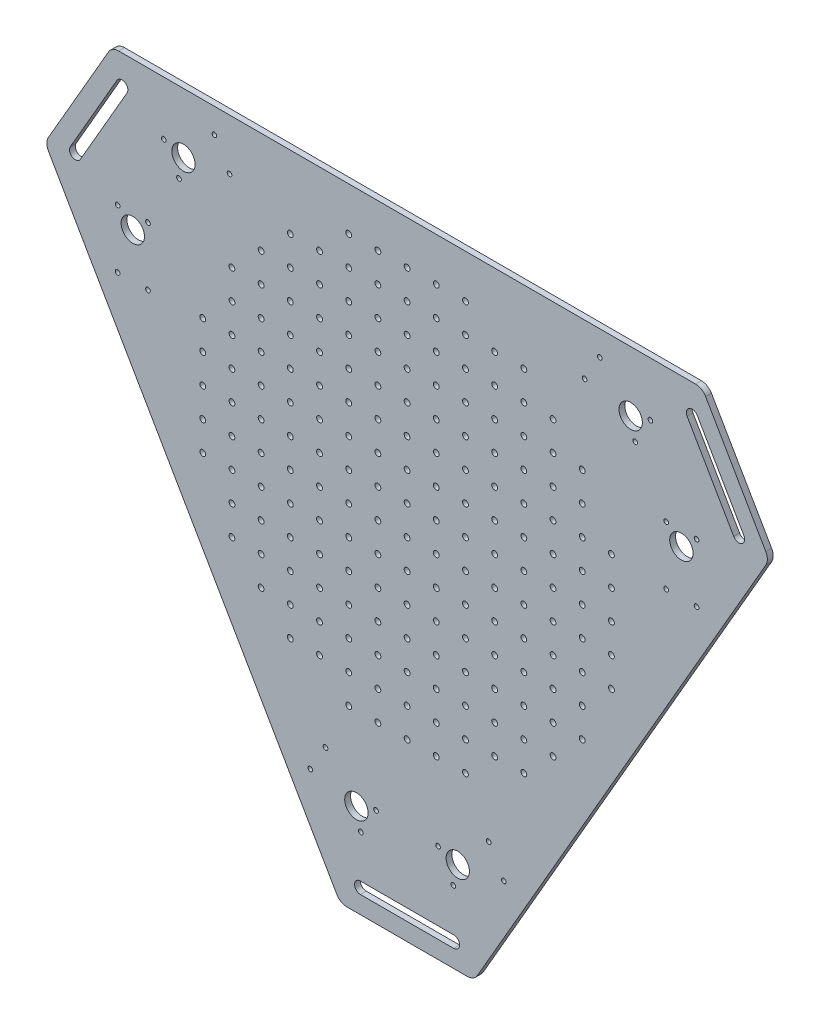
SolidWorks part; units mm, degrees
ref_plane "Piano frontale" through (0, 0, 0) normal (0, 0, 1) x (1, 0, 0)
ref_plane "Piano superiore" through (0, 0, 0) normal (0, 1, 0) x (1, 0, 0)
ref_plane "Piano destro" through (0, 0, 0) normal (1, 0, 0) x (0, 0, -1)
ref_plane "Piano1" through (0, 0, 595) normal (0, 0, -1) x (-1, 0, 0)
sketch "Schizzo1" plane through (0, 0, 595) normal (0, 0, -1) x (-1, 0, 0)
  line L0 (39.9858, -310) -> (-39.9858, -310)
  line L1 (-39.9858, -300) -> (39.9858, -300)
  line L2 (248.475, 189.6287) -> (288.4608, 120.3713)
  line L3 (279.8005, 115.3713) -> (239.8147, 184.6287)
  line L4 (-239.8147, 184.6287) -> (-279.8005, 115.3713)
  line L5 (-288.4608, 120.3713) -> (-248.475, 189.6287)
  line L6 (60.193, -320) -> (307.2246, 107.8713)
  line L7 (307.2246, 117.8713) -> (255.6919, 207.1287)
  line L8 (247.0316, 212.1287) -> (-247.0316, 212.1287)
  line L9 (-255.6919, 207.1287) -> (-307.2246, 117.8713)
  line L10 (-307.2246, 107.8713) -> (-60.193, -320)
  line L11 (-51.5328, -325) -> (51.5328, -325)
  arc A0 (-39.9858, -310) -> (-39.9858, -300) centre (-39.9858, -305) cw
  arc A1 (39.9858, -300) -> (39.9858, -310) centre (39.9858, -305) cw
  arc A2 (288.4608, 120.3713) -> (279.8005, 115.3713) centre (284.1306, 117.8713) cw
  arc A3 (239.8147, 184.6287) -> (248.475, 189.6287) centre (244.1449, 187.1287) cw
  circle A4 centre (-50, -175) radius 2.5
  circle A5 centre (-25, -175) radius 2.5
  circle A6 centre (-100, -150) radius 2.5
  circle A7 centre (-75, -150) radius 2.5
  circle A8 centre (-50, -150) radius 2.5
  circle A9 centre (-25, -150) radius 2.5
  circle A10 centre (-125, -125) radius 2.5
  circle A11 centre (-100, -125) radius 2.5
  circle A12 centre (-75, -125) radius 2.5
  circle A13 centre (-50, -125) radius 2.5
  circle A14 centre (-25, -125) radius 2.5
  circle A15 centre (-150, -100) radius 2.5
  circle A16 centre (-125, -100) radius 2.5
  circle A17 centre (-100, -100) radius 2.5
  circle A18 centre (-75, -100) radius 2.5
  circle A19 centre (-50, -100) radius 2.5
  circle A20 centre (-25, -100) radius 2.5
  circle A21 centre (-150, -75) radius 2.5
  circle A22 centre (-125, -75) radius 2.5
  circle A23 centre (-100, -75) radius 2.5
  circle A24 centre (-75, -75) radius 2.5
  circle A25 centre (-50, -75) radius 2.5
  circle A26 centre (-25, -75) radius 2.5
  circle A27 centre (-175, -50) radius 2.5
  circle A28 centre (-150, -50) radius 2.5
  circle A29 centre (-125, -50) radius 2.5
  circle A30 centre (-100, -50) radius 2.5
  circle A31 centre (-75, -50) radius 2.5
  circle A32 centre (-50, -50) radius 2.5
  circle A33 centre (-25, -50) radius 2.5
  circle A34 centre (-175, -25) radius 2.5
  circle A35 centre (-150, -25) radius 2.5
  circle A36 centre (-125, -25) radius 2.5
  circle A37 centre (-100, -25) radius 2.5
  circle A38 centre (-75, -25) radius 2.5
  circle A39 centre (-50, -25) radius 2.5
  circle A40 centre (-25, -25) radius 2.5
  circle A41 centre (175, -50) radius 2.5
  circle A42 centre (175, -25) radius 2.5
  circle A43 centre (150, -100) radius 2.5
  circle A44 centre (150, -75) radius 2.5
  circle A45 centre (150, -50) radius 2.5
  circle A46 centre (150, -25) radius 2.5
  circle A47 centre (125, -125) radius 2.5
  circle A48 centre (125, -100) radius 2.5
  circle A49 centre (125, -75) radius 2.5
  circle A50 centre (125, -50) radius 2.5
  circle A51 centre (125, -25) radius 2.5
  circle A52 centre (100, -150) radius 2.5
  circle A53 centre (100, -125) radius 2.5
  circle A54 centre (100, -100) radius 2.5
  circle A55 centre (100, -75) radius 2.5
  circle A56 centre (100, -50) radius 2.5
  circle A57 centre (100, -25) radius 2.5
  circle A58 centre (75, -150) radius 2.5
  circle A59 centre (75, -125) radius 2.5
  circle A60 centre (75, -100) radius 2.5
  circle A61 centre (75, -75) radius 2.5
  circle A62 centre (75, -50) radius 2.5
  circle A63 centre (75, -25) radius 2.5
  circle A64 centre (50, -175) radius 2.5
  circle A65 centre (50, -150) radius 2.5
  circle A66 centre (50, -125) radius 2.5
  circle A67 centre (50, -100) radius 2.5
  circle A68 centre (50, -75) radius 2.5
  circle A69 centre (50, -50) radius 2.5
  circle A70 centre (50, -25) radius 2.5
  circle A71 centre (25, -175) radius 2.5
  circle A72 centre (25, -150) radius 2.5
  circle A73 centre (25, -125) radius 2.5
  circle A74 centre (25, -100) radius 2.5
  circle A75 centre (25, -75) radius 2.5
  circle A76 centre (25, -50) radius 2.5
  circle A77 centre (25, -25) radius 2.5
  circle A78 centre (0, -75) radius 2.5
  circle A79 centre (0, -175) radius 2.5
  circle A80 centre (0, -150) radius 2.5
  circle A81 centre (0, -125) radius 2.5
  circle A82 centre (0, -100) radius 2.5
  circle A83 centre (0, -50) radius 2.5
  circle A84 centre (0, -25) radius 2.5
  circle A85 centre (50, 175) radius 2.5
  circle A86 centre (25, 175) radius 2.5
  circle A87 centre (100, 150) radius 2.5
  circle A88 centre (75, 150) radius 2.5
  circle A89 centre (50, 150) radius 2.5
  circle A90 centre (25, 150) radius 2.5
  circle A91 centre (125, 125) radius 2.5
  circle A92 centre (100, 125) radius 2.5
  circle A93 centre (75, 125) radius 2.5
  circle A94 centre (50, 125) radius 2.5
  circle A95 centre (25, 125) radius 2.5
  circle A96 centre (150, 100) radius 2.5
  circle A97 centre (125, 100) radius 2.5
  circle A98 centre (100, 100) radius 2.5
  circle A99 centre (75, 100) radius 2.5
  circle A100 centre (50, 100) radius 2.5
  circle A101 centre (25, 100) radius 2.5
  circle A102 centre (150, 75) radius 2.5
  circle A103 centre (125, 75) radius 2.5
  circle A104 centre (100, 75) radius 2.5
  circle A105 centre (75, 75) radius 2.5
  circle A106 centre (50, 75) radius 2.5
  circle A107 centre (25, 75) radius 2.5
  circle A108 centre (175, 50) radius 2.5
  circle A109 centre (150, 50) radius 2.5
  circle A110 centre (125, 50) radius 2.5
  circle A111 centre (100, 50) radius 2.5
  circle A112 centre (75, 50) radius 2.5
  circle A113 centre (50, 50) radius 2.5
  circle A114 centre (25, 50) radius 2.5
  circle A115 centre (175, 25) radius 2.5
  circle A116 centre (150, 25) radius 2.5
  circle A117 centre (125, 25) radius 2.5
  circle A118 centre (100, 25) radius 2.5
  circle A119 centre (75, 25) radius 2.5
  circle A120 centre (50, 25) radius 2.5
  circle A121 centre (25, 25) radius 2.5
  circle A122 centre (75, 0) radius 2.5
  circle A123 centre (175, 0) radius 2.5
  circle A124 centre (150, 0) radius 2.5
  circle A125 centre (125, 0) radius 2.5
  circle A126 centre (100, 0) radius 2.5
  circle A127 centre (50, 0) radius 2.5
  circle A128 centre (25, 0) radius 2.5
  circle A129 centre (-175, 50) radius 2.5
  circle A130 centre (-175, 25) radius 2.5
  circle A131 centre (-175, 0) radius 2.5
  circle A132 centre (-150, 100) radius 2.5
  circle A133 centre (-150, 75) radius 2.5
  circle A134 centre (-150, 50) radius 2.5
  circle A135 centre (-150, 25) radius 2.5
  circle A136 centre (-150, 0) radius 2.5
  circle A137 centre (-125, 125) radius 2.5
  circle A138 centre (-125, 100) radius 2.5
  circle A139 centre (-125, 75) radius 2.5
  circle A140 centre (-125, 50) radius 2.5
  circle A141 centre (-125, 25) radius 2.5
  circle A142 centre (-125, 0) radius 2.5
  circle A143 centre (-100, 150) radius 2.5
  circle A144 centre (-100, 125) radius 2.5
  circle A145 centre (-100, 100) radius 2.5
  circle A146 centre (-100, 75) radius 2.5
  circle A147 centre (-100, 50) radius 2.5
  circle A148 centre (-100, 25) radius 2.5
  circle A149 centre (-100, 0) radius 2.5
  circle A150 centre (-75, 150) radius 2.5
  circle A151 centre (-75, 125) radius 2.5
  circle A152 centre (-75, 100) radius 2.5
  circle A153 centre (-75, 75) radius 2.5
  circle A154 centre (-75, 50) radius 2.5
  circle A155 centre (-75, 25) radius 2.5
  circle A156 centre (-75, 0) radius 2.5
  circle A157 centre (-50, 175) radius 2.5
  circle A158 centre (-50, 150) radius 2.5
  circle A159 centre (-50, 125) radius 2.5
  circle A160 centre (-50, 100) radius 2.5
  circle A161 centre (-50, 75) radius 2.5
  circle A162 centre (-50, 50) radius 2.5
  circle A163 centre (-50, 25) radius 2.5
  circle A164 centre (-50, 0) radius 2.5
  circle A165 centre (-25, 175) radius 2.5
  circle A166 centre (-25, 150) radius 2.5
  circle A167 centre (-25, 125) radius 2.5
  circle A168 centre (-25, 100) radius 2.5
  circle A169 centre (-25, 75) radius 2.5
  circle A170 centre (-25, 50) radius 2.5
  circle A171 centre (-25, 25) radius 2.5
  circle A172 centre (-25, 0) radius 2.5
  circle A173 centre (0, 75) radius 2.5
  circle A174 centre (0, 175) radius 2.5
  circle A175 centre (0, 150) radius 2.5
  circle A176 centre (0, 125) radius 2.5
  circle A177 centre (0, 100) radius 2.5
  circle A178 centre (0, 50) radius 2.5
  circle A179 centre (0, 25) radius 2.5
  circle A180 centre (0, 0) radius 2.5
  circle A181 centre (-208.3566, 165.9823) radius 2
  circle A182 centre (-195.3566, 143.4656) radius 2
  circle A183 centre (-165.0553, 190.9823) radius 2
  circle A184 centre (-152.0553, 168.4656) radius 2
  circle A185 centre (69.8679, -215.9166) radius 2
  circle A186 centre (82.8679, -238.4332) radius 2
  circle A187 centre (26.5666, -240.9166) radius 2
  circle A188 centre (39.5666, -263.4332) radius 2
  circle A189 centre (-39.5666, -263.4332) radius 2
  circle A190 centre (-26.5666, -240.9166) radius 2
  circle A191 centre (-82.8679, -238.4332) radius 2
  circle A192 centre (-69.8679, -215.9166) radius 2
  circle A193 centre (152.0553, 168.4656) radius 2
  circle A194 centre (165.0553, 190.9823) radius 2
  circle A195 centre (195.3566, 143.4656) radius 2
  circle A196 centre (208.3566, 165.9823) radius 2
  circle A197 centre (247.9232, 97.451) radius 2
  circle A198 centre (221.9232, 97.451) radius 2
  circle A199 centre (247.9232, 47.4509) radius 2
  circle A200 centre (221.9232, 47.4509) radius 2
  circle A201 centre (-221.9232, 47.4509) radius 2
  circle A202 centre (-247.9232, 47.4509) radius 2
  circle A203 centre (-221.9232, 97.451) radius 2
  circle A204 centre (-247.9232, 97.451) radius 2
  circle A205 centre (-234.9232, 85.505) radius 10
  circle A206 centre (-191.5111, 160.6969) radius 10
  circle A207 centre (191.5111, 160.6969) radius 10
  circle A208 centre (234.9232, 85.505) radius 10
  circle A209 centre (43.412, -246.2019) radius 10
  circle A210 centre (-43.412, -246.2019) radius 10
  arc A211 (-248.475, 189.6287) -> (-239.8147, 184.6287) centre (-244.1449, 187.1287) cw
  arc A212 (-279.8005, 115.3713) -> (-288.4608, 120.3713) centre (-284.1306, 117.8713) cw
  arc A213 (307.2246, 107.8713) -> (307.2246, 117.8713) centre (298.5644, 112.8713) ccw
  arc A214 (255.6919, 207.1287) -> (247.0316, 212.1287) centre (247.0316, 202.1287) ccw
  arc A215 (-247.0316, 212.1287) -> (-255.6919, 207.1287) centre (-247.0316, 202.1287) ccw
  arc A216 (-307.2246, 117.8713) -> (-307.2246, 107.8713) centre (-298.5644, 112.8713) ccw
  arc A217 (-60.193, -320) -> (-51.5328, -325) centre (-51.5328, -315) ccw
  arc A218 (51.5328, -325) -> (60.193, -320) centre (51.5328, -315) ccw
extrude "Estrusione-Estrusione1" add sketch "Schizzo1" against normal blind 5
